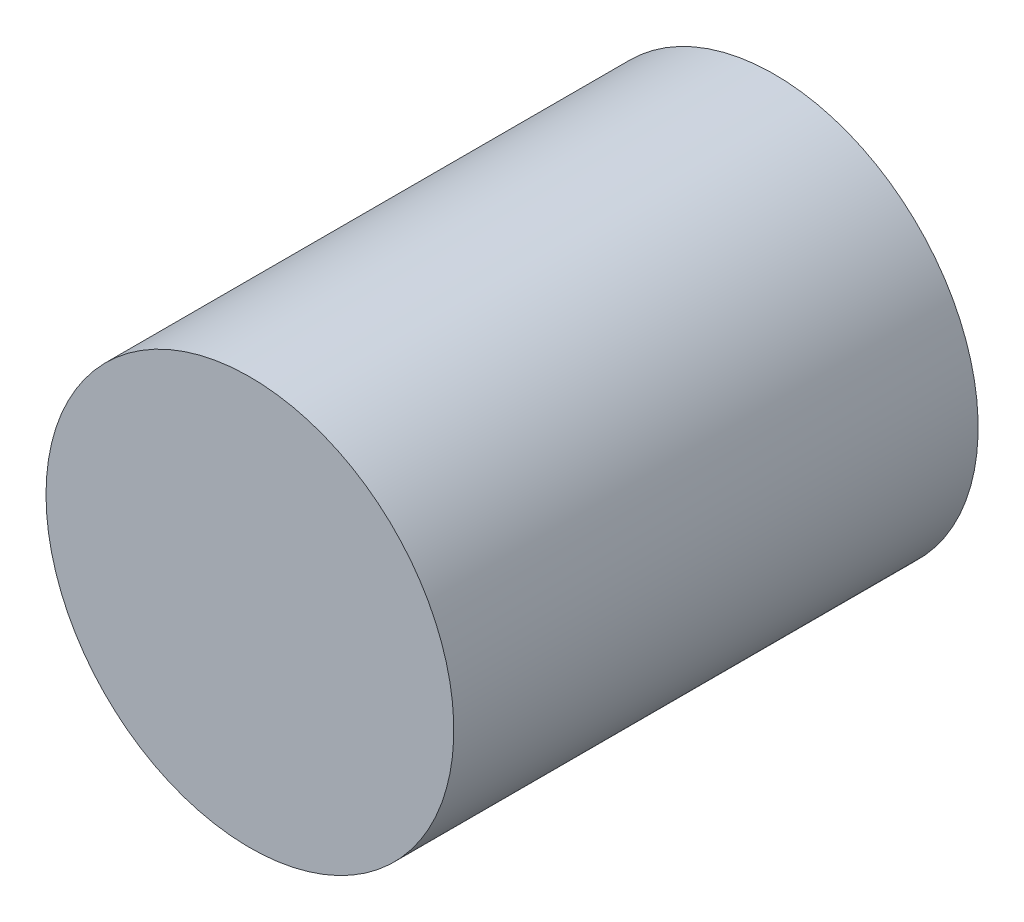
SolidWorks part; units mm, degrees
ref_plane "Front Plane" through (0, 0, 0) normal (0, 0, 1) x (1, 0, 0)
ref_plane "Top Plane" through (0, 0, 0) normal (0, 1, 0) x (1, 0, 0)
ref_plane "Right Plane" through (0, 0, 0) normal (1, 0, 0) x (0, 0, -1)
sketch "Sketch1" plane through (0, 0, 0) normal (0, 0, 1) x (1, 0, 0)
  circle A0 centre (0, 0) radius 17.5
  dimension "D1" = 35
extrude "Boss-Extrude1" add sketch "Sketch1" along normal blind 45
